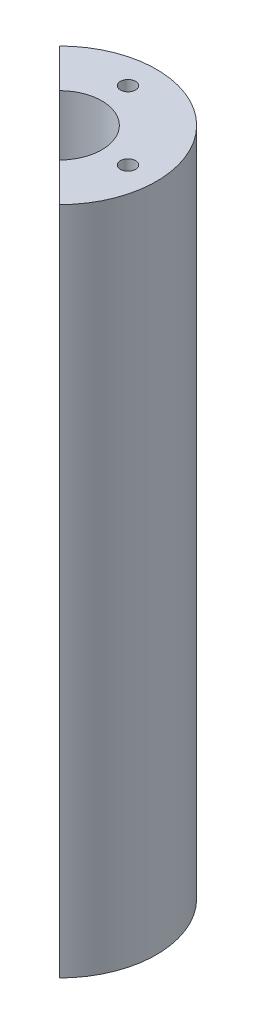
SolidWorks part; units mm, degrees
ref_plane "Front" through (0, 0, 0) normal (0, 0, 1) x (1, 0, 0)
ref_plane "Top" through (0, 0, 0) normal (0, 1, 0) x (1, 0, 0)
ref_plane "Right" through (0, 0, 0) normal (1, 0, 0) x (0, 0, -1)
sketch "Sketch1" plane through (0, 0, 0) normal (0, 1, 0) x (1, 0, 0)
  line L0 (0, 0) -> (-11.3137, 11.3137)
  line L1 (0, 0) -> (11.3137, -11.3137)
  circle A0 centre (0, 0) radius 16
  circle A1 centre (0, 0) radius 7
  circle A2 centre (0, 0) radius 11.3137
  circle A3 centre (0, 11.3137) radius 1.25
  circle A4 centre (11.3137, 0) radius 1.25
extrude "Boss-Extrude1" add sketch "Sketch1" along normal blind 110.3 contours A4 A2 A3 L0 A1 L1 | A4 A2 L1 A0 L0 A3
